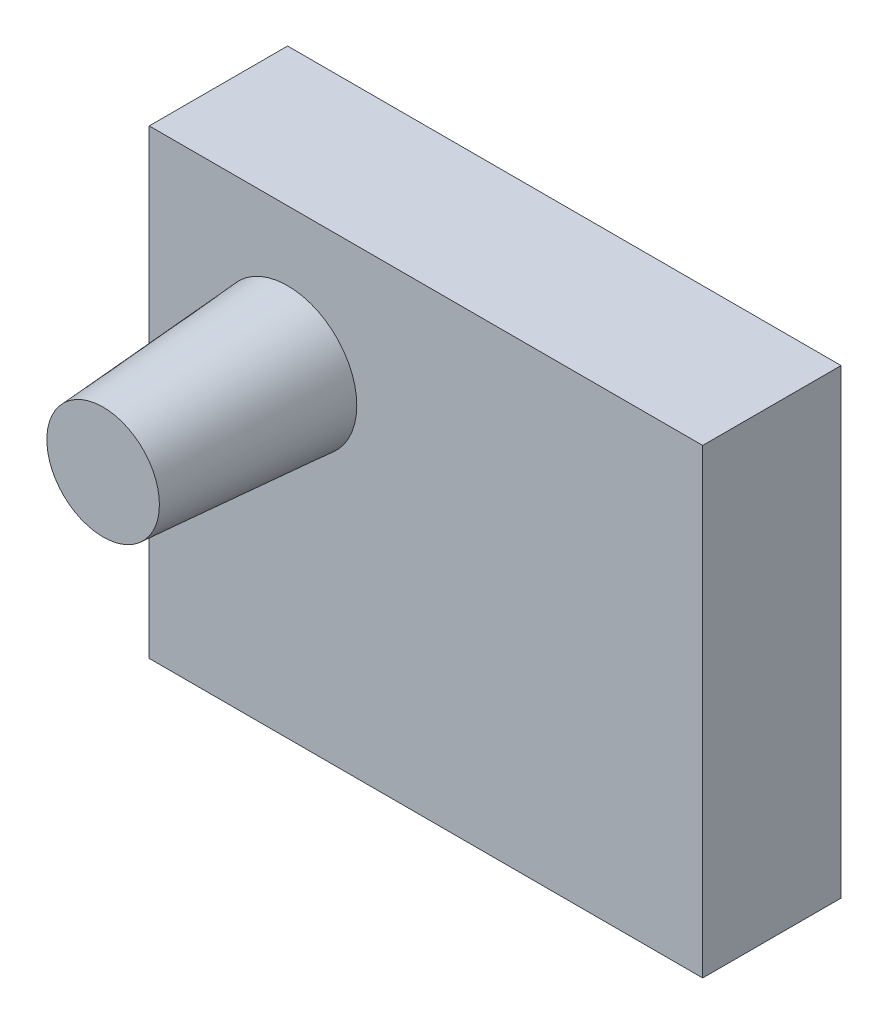
SolidWorks part; units mm, degrees
ref_plane "Alzado" through (0, 0, 0) normal (0, 0, 1) x (1, 0, 0)
ref_plane "Planta" through (0, 0, 0) normal (0, 1, 0) x (1, 0, 0)
ref_plane "Vista lateral" through (0, 0, 0) normal (1, 0, 0) x (0, 0, -1)
sketch "Croquis1" plane through (0, 0, 0) normal (0, 0, 1) x (1, 0, 0)
  line L1 (0, 0) -> (120, 0)
  line L2 (0, 0) -> (0, 100)
  line L3 (0, 100) -> (120, 100)
  line L4 (120, 0) -> (120, 100)
  dimension "D1" = 100
  dimension "D2" = 120
extrude "Saliente-Extruir1" add sketch "Croquis1" along normal blind 30 contours L2 L1 L4 L3
sketch "Croquis3" plane through (0, 0, 30) normal (0, 0, 1) x (1, 0, 0)
  line L0 (0, 100) -> (120, 100) construction
  line L1 (0, 0) -> (0, 100) construction
  circle A0 centre (30, 70) radius 15
  point P4 (0, 0)
  dimension "D1" = 30
  dimension "D2" = 30
extrude "Saliente-Extruir3" add sketch "Croquis3" along normal blind 40 draft 4 contours A0
